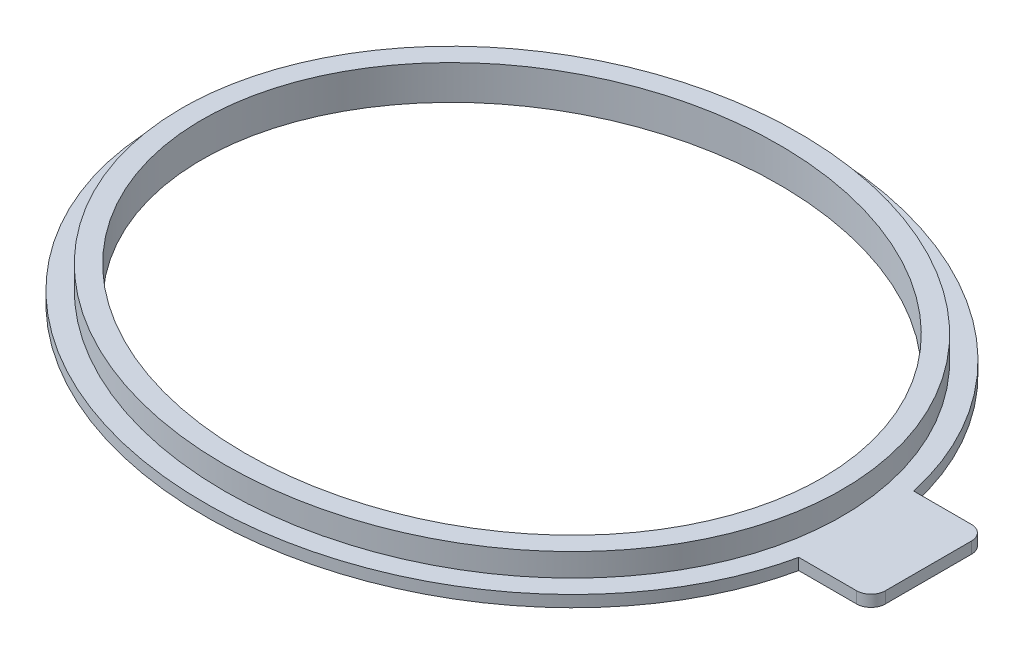
SolidWorks part; units mm, degrees
ref_plane "Front Plane" through (0, 0, 0) normal (0, 0, 1) x (1, 0, 0)
ref_plane "Top Plane" through (0, 0, 0) normal (0, 1, 0) x (1, 0, 0)
ref_plane "Right Plane" through (0, 0, 0) normal (1, 0, 0) x (0, 0, -1)
sketch "Sketch1" plane through (0, 0, 0) normal (0, 1, 0) x (1, 0, 0)
  ellipse E0 centre (0, 0) end of major axis (108, 0) minor radius 93
  ellipse E1 centre (0, 0) end of major axis (-115, 0) minor radius 100
extrude "Boss-Extrude1" add sketch "Sketch1" along normal blind 12
sketch "Sketch2" plane through (0, 0, 0) normal (0, 1, 0) x (1, 0, 0)
  ellipse E0 centre (0, 0) end of major axis (-122, 0) minor radius 107
  ellipse E1 centre (0, 0) end of major axis (-108, 0) minor radius 93
  ellipse E2 centre (0, 0) end of major axis (108, 0) minor radius 93 construction
extrude "Boss-Extrude2" add sketch "Sketch2" along normal blind 4
sketch "Sketch3" plane through (0, 0, 0) normal (0, 1, 0) x (1, 0, 0)
  line L0 (0, 0) -> (115, 0)
  line L1 (115, 0) -> (115, 20)
  line L2 (115, 0) -> (115, -20)
  line L3 (115, 20) -> (145, 20)
  line L4 (115, -20) -> (145, -20)
  line L5 (145, -20) -> (145, 20)
  ellipse E0 centre (0, 0) end of major axis (-115, 0) minor radius 100 construction
  ellipse E1 centre (0, 0) end of major axis (-115, 0) minor radius 100 construction
  dimension "D1" = 20
  dimension "D2" = 20
  dimension "D3" = 30
extrude "Boss-Extrude3" add sketch "Sketch3" along normal blind 4 contours L4 L5 L3 L1 L2
fillet "Fillet1" radius 5 2 edges at (145, 2, -20) (145, 2, 20)
